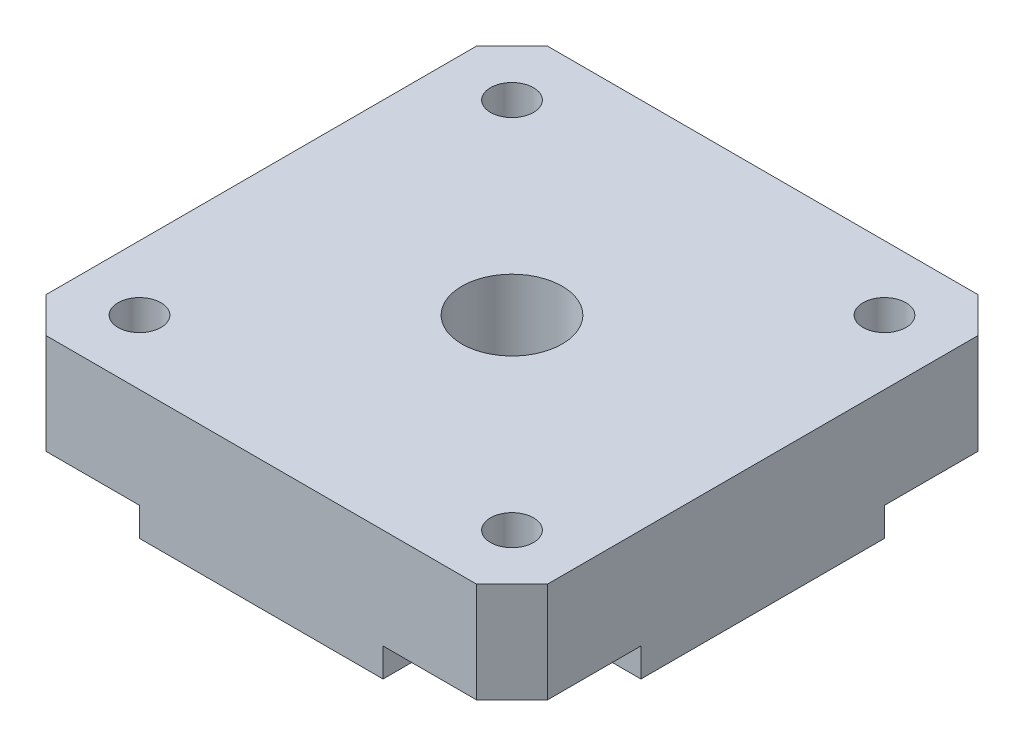
SolidWorks part; units mm, degrees
material "Aleación 1060"
ref_plane "Alzado" through (0, 0, 0) normal (0, 0, 1) x (1, 0, 0)
ref_plane "Planta" through (0, 0, 0) normal (0, 1, 0) x (1, 0, 0)
ref_plane "Vista lateral" through (0, 0, 0) normal (1, 0, 0) x (0, 0, -1)
sketch "Croquis1" plane through (0, 0, 0) normal (0, 1, 0) x (1, 0, 0)
  line L0 (0, 2.4731) -> (2.4731, 0)
  line L1 (2.4731, 0) -> (32.5269, 0)
  line L2 (32.5269, 0) -> (35, 2.4731)
  line L3 (35, 2.4731) -> (35, 32.5269)
  line L4 (35, 32.5269) -> (32.5269, 35)
  line L5 (32.5269, 35) -> (2.4731, 35)
  line L6 (2.4731, 35) -> (0, 32.5269)
  line L7 (0, 32.5269) -> (0, 2.4731)
  dimension "D1" = 35
  dimension "D2" = 35
  dimension "D3" = 46
  dimension "D4" = 46
  dimension "D5" = 45
extrude "Saliente-Extruir1" add sketch "Croquis1" along normal blind 9
sketch "Croquis2" plane through (0, 9, 0) normal (0, 1, 0) x (1, 0, 0)
  line L0 (17.5, 35) -> (17.5, 0) construction
  line L1 (32.5269, 35) -> (2.4731, 35) construction
  line L2 (2.4731, 0) -> (32.5269, 0) construction
  circle A0 centre (17.5, 17.5) radius 3.5
  dimension "D1" = 7
extrude "Cortar-Extruir1" cut sketch "Croquis2" against normal through all
sketch "Croquis3" plane through (0, 9, 0) normal (0, 1, 0) x (1, 0, 0)
  line L0 (4.5, 30.5) -> (30.5, 4.5) construction
  line L1 (4.5, 30.5) -> (30.5, 30.5) construction
  line L2 (4.5, 30.5) -> (4.5, 4.5) construction
  line L3 (4.5, 4.5) -> (30.5, 4.5) construction
  line L4 (30.5, 30.5) -> (30.5, 4.5) construction
  line L5 (4.5, 4.5) -> (30.5, 30.5) construction
  circle A0 centre (4.5, 30.5) radius 1.5
  circle A1 centre (30.5, 30.5) radius 1.5
  circle A2 centre (30.5, 4.5) radius 1.5
  circle A3 centre (4.5, 4.5) radius 1.5
  point P4 (17.5, 17.5)
  point P5 (17.5, 17.5)
  point P17 (17.5, 17.5)
  dimension "D3" = 3
  dimension "D1" = 26
  dimension "D2" = 26
  dimension "D4" = 4
extrude "Cortar-Extruir2" cut sketch "Croquis3" against normal through all
sketch "Sketch1" plane through (0, 0, 0) normal (0, -1, 0) x (1, 0, 0)
  line L0 (35, 0) -> (35, -9)
  line L1 (0, 0) -> (9, 0)
  line L2 (0, 0) -> (0, -9)
  line L3 (0, -9) -> (5, -9)
  line L4 (9, 0) -> (9, -5)
  line L5 (35, 0) -> (26, 0)
  line L6 (26, 0) -> (26, -5)
  line L7 (35, -9) -> (30, -9)
  line L8 (35, -35) -> (26, -35)
  line L9 (35, -35) -> (35, -26)
  line L10 (35, -26) -> (30, -26)
  line L11 (26, -35) -> (26, -30)
  line L12 (0, -35) -> (0, -26)
  line L13 (0, -35) -> (9, -35)
  line L14 (9, -35) -> (9, -30)
  line L15 (0, -26) -> (5, -26)
  arc A0 (5, -9) -> (9, -5) centre (5, -5) ccw
  arc A1 (26, -5) -> (30, -9) centre (30, -5) ccw
  arc A2 (30, -26) -> (26, -30) centre (30, -30) ccw
  arc A3 (9, -30) -> (5, -26) centre (5, -30) ccw
  point P7 (9, -9)
  point P8 (17.5, -17.5)
  point P31 (17.5, -17.5)
  dimension "D2" = 4
  dimension "D1" = 9
  dimension "D3" = 4
extrude "Cut-Extrude1" cut sketch "Sketch1" against normal blind 2
